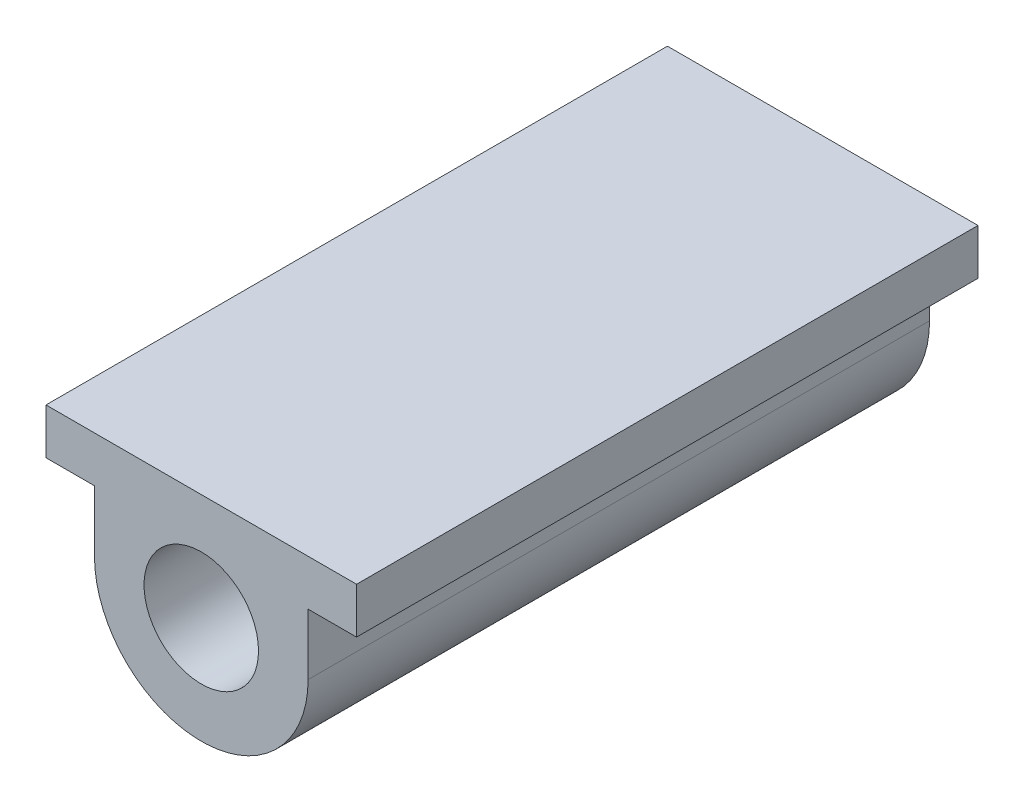
SolidWorks part; units mm, degrees
ref_plane "Front Plane" through (0, 0, 0) normal (0, 0, 1) x (1, 0, 0)
ref_plane "Top Plane" through (0, 0, 0) normal (0, 1, 0) x (1, 0, 0)
ref_plane "Right Plane" through (0, 0, 0) normal (1, 0, 0) x (0, 0, -1)
sketch "Sketch1" plane through (0, 0, 0) normal (0, 0, 1) x (1, 0, 0)
  line L0 (-20.35, 14) -> (20.35, 14)
  line L1 (20.35, 14) -> (20.35, 8)
  line L2 (20.35, 8) -> (14, 8)
  line L3 (14, 8) -> (14, 0)
  line L4 (-20.35, 14) -> (-20.35, 8)
  line L5 (-20.35, 8) -> (-14, 8)
  line L6 (-14, 8) -> (-14, 0)
  line L7 (0, 0) -> (0, 14) construction
  arc A0 (14, 0) -> (-14, 0) centre (0, 0) cw
  circle A1 centre (0, 0) radius 7.5
  dimension "D3" = 14
  dimension "D5" = 15
  dimension "D1" = 40.7
  dimension "D2" = 6
  dimension "D4" = 8
extrude "Boss-Extrude1" add sketch "Sketch1" along normal blind 81.44
